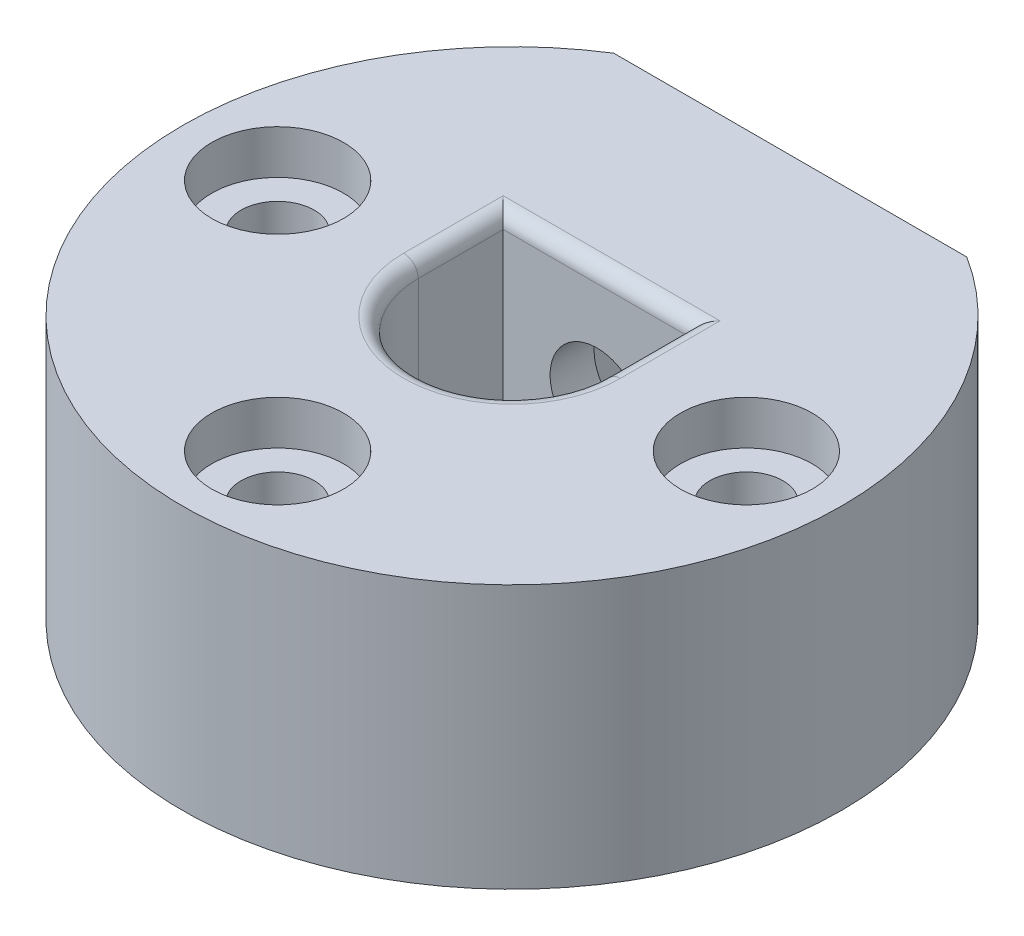
SolidWorks part; units mm, degrees
ref_plane "Plan de face" through (0, 0, 0) normal (0, 0, 1) x (1, 0, 0)
ref_plane "Plan de dessus" through (0, 0, 0) normal (0, 1, 0) x (1, 0, 0)
ref_plane "Plan de droite" through (0, 0, 0) normal (1, 0, 0) x (0, 0, -1)
sketch "Esquisse1" plane through (0, 0, 0) normal (0, 1, 0) x (1, 0, 0)
  line L1 (-3.2, 0) -> (-3.2, 2.9)
  line L2 (3.2, 0) -> (3.2, 2.9)
  line L3 (3.2, 2.9) -> (-3.2, 2.9)
  line L4 (6.026, 9.5) -> (-6.026, 9.5)
  arc A0 (-6.026, 9.5) -> (6.026, 9.5) centre (0, 0) ccw
  arc A1 (-3.2, 0) -> (3.2, 0) centre (0, 0) ccw
  point P10 (0, 2.9)
  dimension "D1" = 22.5
  dimension "D2" = 6.4
  dimension "D3" = 2.9
  dimension "D4" = 9.5
extrude "Boss.-Extru.1" add sketch "Esquisse1" along normal blind 9
hole_wizard "Chambrage pour vis à tête cylindrique à 6 pans creux (ou vis CHC) M21" positions "Esquisse2" profile "Esquisse3" counterbore size "M2" standard "Ansi Metric" end condition through all
sketch "Esquisse2" plane through (0, 9, 0) normal (0, 1, 0) x (1, 0, 0)
  line L0 (0, 0) -> (6.1221, 0) construction
  line L2 (0, 0) -> (13.3941, 0) construction
  point P0 (8, 0)
  point P28 (-8, 0)
  point P31 (0, 0)
  point P36 (0, -8)
  point P37 (0, 0)
  dimension "D1" = 8
  dimension "D3" = 0
  dimension "D2" = 2
  dimension "D4" = 2
sketch "Esquisse3" plane through (8, 9, 0) normal (1, 0, 0) x (0, 0, 1)
  line L0 (0, 0) -> (0, 9)
  line L1 (0, 9) -> (1.25, 9)
  line L3 (1.25, 9) -> (1.25, 1.5)
  line L4 (1.25, 1.5) -> (2.25, 1.5)
  line L5 (2.25, 1.5) -> (2.25, 0)
  line L7 (2.25, 0) -> (0, 0)
  line L11 (0, -6.35) -> (0, 107.95) construction
  dimension "Diamètre du perçage jusqu'au prochain" = 2.5
  dimension "Profondeur du perçage jusqu'au prochain" = 9
  dimension "Diamètre du chambrage" = 4.5
  dimension "Profondeur du chambrage" = 1.5
fillet "Congé1" radius 0.5 4 edges at (0, 9, 3.2) (-3.2, 9, -1.45) (3.2, 9, -1.45) (0, 9, -2.9)
sketch "Esquisse6" plane through (0, 0, 0) normal (0, 0, 1) x (1, 0, 0)
  line L0 (0, 0) -> (0, 9) construction
  line L1 (11.25, 9) -> (-11.25, 9) construction
  line L2 (11.25, 9) -> (-11.25, 9) construction
  circle A0 centre (0, 5) radius 1.6
  dimension "D1" = 3.2
  dimension "D2" = 4
extrude "Enlèv. mat.-Extru.1" cut sketch "Esquisse6" against normal through all
sketch "Esquisse7" plane through (0, 0, 0) normal (0, 1, 0) x (1, 0, 0)
  line L1 (-2.925, 4.4) -> (2.925, 4.4)
  line L2 (-2.925, 4.4) -> (-2.925, 6.65)
  line L3 (-2.925, 6.65) -> (2.925, 6.65)
  line L4 (2.925, 4.4) -> (2.925, 6.65)
  line L5 (-2.925, 4.4) -> (2.925, 6.65) construction
  line L6 (-2.925, 6.65) -> (2.925, 4.4) construction
  line L7 (3.2, 2.9) -> (-3.2, 2.9) construction
  point P0 (0, 5.525)
  dimension "D3" = 1.5
  dimension "D1" = 2.25
  dimension "D2" = 5.85
extrude "Enlèv. mat.-Extru.2" cut sketch "Esquisse7" along normal blind 7.25
